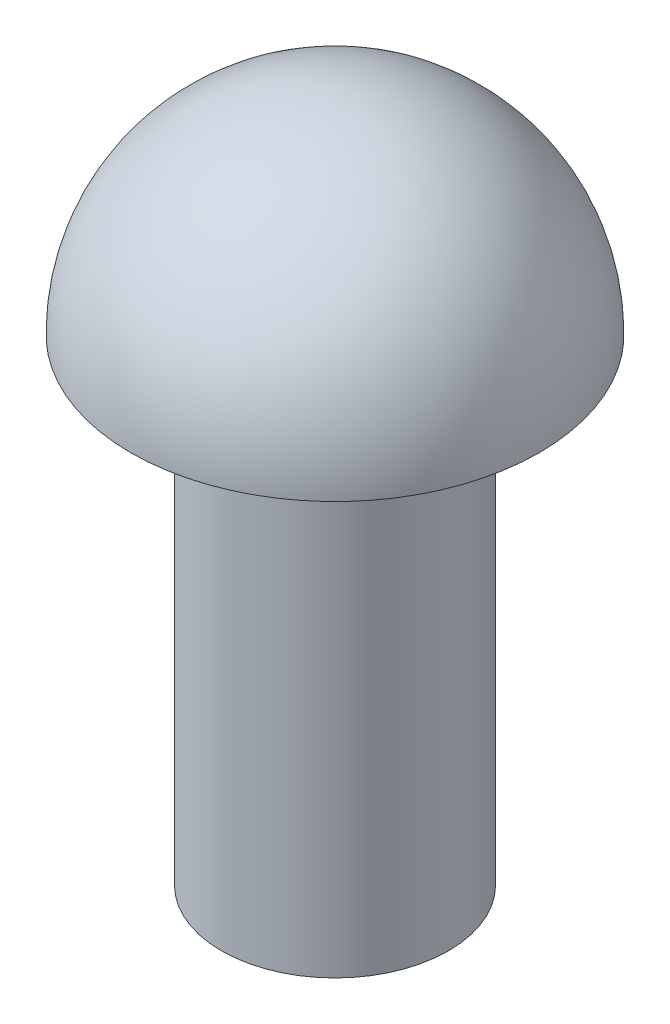
SolidWorks part; units mm, degrees
material "Pine"
ref_plane "Front" through (0, 0, 0) normal (0, 0, 1) x (1, 0, 0)
ref_plane "Top" through (0, 0, 0) normal (0, 1, 0) x (1, 0, 0)
ref_plane "Right" through (0, 0, 0) normal (1, 0, 0) x (0, 0, -1)
sketch "Sketch1" plane through (0, 0, 0) normal (0, 1, 0) x (1, 0, 0)
  circle A0 centre (0, 0) radius 5
  dimension "D1" = 10
extrude "Boss-Extrude1" add sketch "Sketch1" against normal blind 21
sketch "Sketch3" plane through (0, 0, 0) normal (0, 1, 0) x (-1, 0, 0)
  circle A0 centre (0, 0) radius 6
  dimension "D1" = 12
extrude "Cut-Extrude1" [suppressed] cut sketch "Sketch3" against normal blind 20 flip side to cut
sketch "Sketch4" plane through (0, -21, 0) normal (0, -1, 0) x (-1, 0, 0)
  circle A0 centre (0, 0) radius 5
  dimension "D1" = 10
extrude "Cut-Extrude2" [suppressed] cut sketch "Sketch4" against normal through all both and the other way through all
sketch "Sketch2" plane through (0, 0, 0) normal (0, 0, 1) x (1, 0, 0)
  line L1 (9, 0) -> (0, 0)
  line L2 (0, 9) -> (0, 0) construction
  line L3 (0, 0) -> (0, 9)
  arc A0 (9, 0) -> (0, 9) centre (0, 0) ccw
  dimension "D1" = 9
revolve "Revolve1" add sketch "Sketch2" angle 360 about L2
